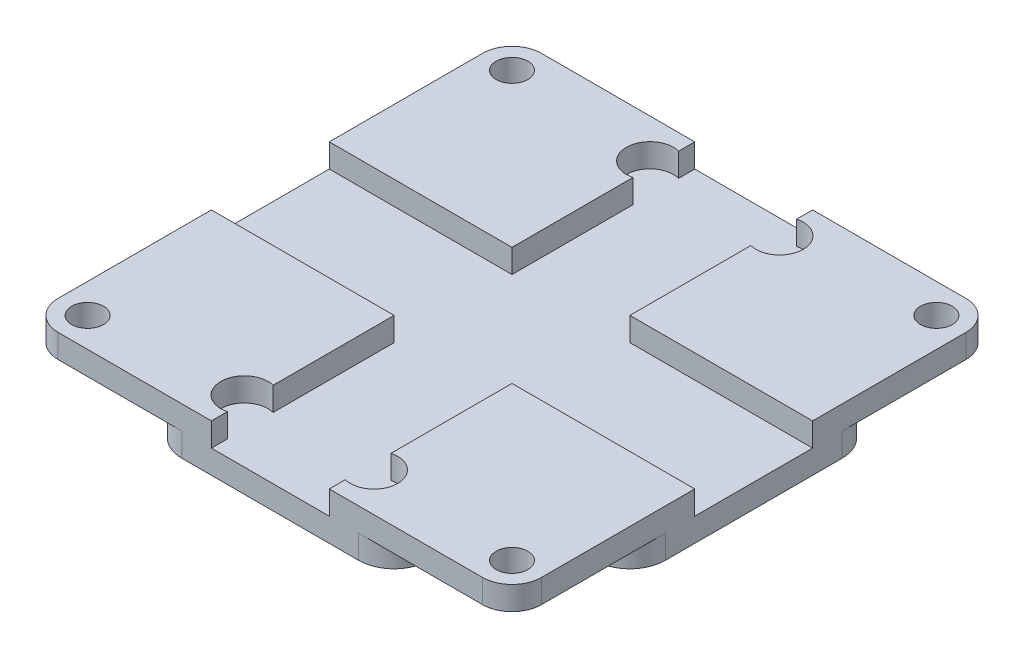
SolidWorks part; units mm, degrees
ref_plane "前视基准面" through (0, 0, 0) normal (0, 0, 1) x (1, 0, 0)
ref_plane "上视基准面" through (0, 0, 0) normal (0, 1, 0) x (1, 0, 0)
ref_plane "右视基准面" through (0, 0, 0) normal (1, 0, 0) x (0, 0, -1)
other "Configuration Table"
sketch "草图1" plane through (0, 0, 0) normal (0, 1, 0) x (1, 0, 0)
  line L1 (2.5, 0) -> (38.5, 0)
  line L2 (0, 2.5) -> (0, 38.5)
  line L3 (2.5, 41) -> (38.5, 41)
  line L4 (41, 2.5) -> (41, 38.5)
  arc A0 (38.5, 0) -> (41, 2.5) centre (38.5, 2.5) ccw
  arc A1 (0, 38.5) -> (2.5, 41) centre (2.5, 38.5) cw
  arc A2 (38.5, 41) -> (41, 38.5) centre (38.5, 38.5) cw
  arc A3 (2.5, 0) -> (0, 2.5) centre (2.5, 2.5) cw
  point P7 (41, 0)
  point P10 (0, 41)
  point P15 (0, 0)
  dimension "D3" = 2.5
  dimension "D1" = 41
  dimension "D2" = 41
extrude "凸台-拉伸1" add sketch "草图1" against normal blind 4 contours L2 A1 L3 A2 L4 A0 L1 A3
sketch "草图2" plane through (0, -4, 0) normal (0, -1, 0) x (1, 0, 0)
  line L0 (20.5, 0) -> (20.5, -41) construction
  line L5 (2.5, 0) -> (0, 0) construction
  line L6 (0, -2.5) -> (0, -38.5) construction
  line L7 (2.5, -41) -> (38.5, -41) construction
  line L8 (2.5, 0) -> (2.5, -2.5) construction
  line L9 (2.5, -2.5) -> (0, -2.5) construction
  line L10 (0, 0) -> (0, -2.5) construction
  line L11 (0, 0) -> (2.5, 0) construction
  line L12 (0, 0) -> (0, -2.5) construction
  line L13 (0, -2.5) -> (2.5, -2.5) construction
  line L14 (2.5, 0) -> (2.5, -2.5) construction
  line L15 (2.5, 0) -> (38.5, 0) construction
  line L16 (41, -20.5) -> (0, -20.5) construction
  line L17 (41, -2.5) -> (41, -38.5) construction
  circle A0 centre (2.5, -2.5) radius 1.35
  circle A1 centre (38.5, -2.5) radius 1.35
  circle A2 centre (2.5, -38.5) radius 1.35
  circle A3 centre (38.5, -38.5) radius 1.35
  point P20 (20.5, -20.5)
extrude "切除-拉伸1" cut sketch "草图2" against normal blind 4
sketch "草图3" plane through (0, -4, 0) normal (0, -1, 0) x (1, 0, 0)
  line L0 (0, -10) -> (0, -13)
  line L1 (0, 0) -> (10, 0)
  line L2 (0, 0) -> (0, -10)
  line L3 (3, -10) -> (7, -10)
  line L4 (10, -3) -> (10, -7)
  line L5 (0, -2.5) -> (0, -38.5) construction
  line L6 (38.5, -2.5) -> (2.5, -38.5) construction
  line L7 (10, 0) -> (13, 0)
  line L9 (10, -3) -> (13, -3) construction
  line L10 (13, 0) -> (13, -3) construction
  line L11 (36, -36) -> (5, -5) construction
  line L12 (41, 0) -> (41, -10)
  line L13 (41, -10) -> (41, -13)
  line L14 (38, -10) -> (34, -10)
  line L15 (31, -3) -> (31, -7)
  line L16 (31, 0) -> (28, 0)
  line L17 (41, 0) -> (31, 0)
  line L18 (41, -41) -> (31, -41)
  line L19 (31, -41) -> (28, -41)
  line L20 (31, -38) -> (31, -34)
  line L21 (38, -31) -> (34, -31)
  line L22 (41, -31) -> (41, -28)
  line L23 (41, -41) -> (41, -31)
  line L24 (0, -41) -> (0, -31)
  line L25 (0, -31) -> (0, -28)
  line L26 (3, -31) -> (7, -31)
  line L27 (10, -38) -> (10, -34)
  line L28 (10, -41) -> (13, -41)
  line L29 (0, -41) -> (10, -41)
  arc A0 (7, -10) -> (10, -7) centre (7, -7) ccw
  arc A1 (3, -10) -> (0, -13) centre (3, -13) ccw
  arc A2 (13, 0) -> (10, -3) centre (13, -3) ccw
  circle A3 centre (20.5, -20.5) radius 0.7475 construction
  arc A4 (41, -13) -> (38, -10) centre (38, -13) ccw
  arc A5 (31, -7) -> (34, -10) centre (34, -7) ccw
  arc A6 (31, -3) -> (28, 0) centre (28, -3) ccw
  arc A7 (28, -41) -> (31, -38) centre (28, -38) ccw
  arc A8 (34, -31) -> (31, -34) centre (34, -34) ccw
  arc A9 (38, -31) -> (41, -28) centre (38, -28) ccw
  arc A10 (0, -28) -> (3, -31) centre (3, -28) ccw
  arc A11 (10, -34) -> (7, -31) centre (7, -34) ccw
  arc A12 (10, -38) -> (13, -41) centre (13, -38) ccw
  point P7 (10, -10)
  point P65 (20.5, -20.5)
  dimension "D3" = 3
  dimension "D1" = 10
  dimension "D2" = 10
  dimension "D4" = 4
extrude "切除-拉伸2" cut sketch "草图3" against normal blind 2
sketch "草图4" plane through (0, 0, 0) normal (0, 1, 0) x (1, 0, 0)
  line L0 (36, 36) -> (5, 5) construction
  line L1 (5, 36) -> (36, 5) construction
  line L2 (-2.5, 15.5) -> (43.5, 15.5)
  line L3 (-2.5, 15.5) -> (-2.5, 25.5)
  line L4 (43.5, 15.5) -> (43.5, 25.5)
  line L5 (-2.5, 25.5) -> (43.5, 25.5)
  line L6 (-2.5, 15.5) -> (43.5, 25.5) construction
  line L7 (43.5, 15.5) -> (-2.5, 25.5) construction
  line L8 (2.5, 0) -> (38.5, 0) construction
  point P8 (20.5, 20.5)
  point P9 (0, 0)
  point P10 (20.5, 20.5)
  point P11 (0, 0)
  point P12 (0, 0)
  dimension "D1" = 5
  dimension "D2" = 15.5
extrude "切除-拉伸3" cut sketch "草图4" against normal blind 2
sketch "草图6" plane through (0, 0, 0) normal (0, 1, 0) x (1, 0, 0)
  line L0 (5, 36) -> (36, 5) construction
  line L1 (36, 36) -> (5, 5) construction
  line L2 (15.5, 15.5) -> (25.5, 15.5) construction
  line L3 (15.5, 15.5) -> (15.5, 25.5) construction
  line L4 (25.5, 15.5) -> (25.5, 25.5) construction
  line L5 (15.5, 25.5) -> (25.5, 25.5) construction
  line L6 (0, 25.5) -> (0, 15.5)
  line L7 (0, 15.5) -> (41, 15.5)
  line L8 (41, 15.5) -> (41, 25.5)
  line L9 (41, 25.5) -> (0, 25.5)
  line L10 (0, 25.5) -> (0, 15.5) construction
  line L11 (0, 15.5) -> (41, 15.5) construction
  line L12 (41, 15.5) -> (41, 25.5) construction
  line L13 (41, 25.5) -> (0, 25.5) construction
  line L14 (15.5, 15.5) -> (25.5, 25.5) construction
  line L15 (25.5, 15.5) -> (15.5, 25.5) construction
  line L16 (25.5, 20.5) -> (15.5, 20.5) construction
  line L17 (15.5, 25.5) -> (25.5, 25.5)
  line L18 (15.5, 25.5) -> (15.5, 50.5)
  line L19 (15.5, 50.5) -> (25.5, 50.5)
  line L20 (25.5, 25.5) -> (25.5, 50.5)
  line L21 (15.5, -9.5) -> (25.5, -9.5)
  line L22 (25.5, 15.5) -> (25.5, -9.5)
  line L23 (15.5, 15.5) -> (25.5, 15.5)
  line L24 (15.5, 15.5) -> (15.5, -9.5)
  line L25 (41, 2.5) -> (41, 15.5) construction
  line L26 (0, 15.5) -> (41, 15.5) construction
  point P8 (20.5, 20.5)
  point P13 (20.5, 20.5)
  dimension "D2" = 35
  dimension "D1" = 0
extrude "切除-拉伸4" cut sketch "草图6" against normal blind 2
sketch "草图7" plane through (0, 0, 0) normal (0, 1, 0) x (1, 0, 0)
  line L0 (36, 36) -> (5, 5) construction
  line L1 (0, 38.5) -> (2.5, 38.5) construction
  line L2 (0, 38.5) -> (0, 41) construction
  line L3 (0, 41) -> (2.5, 41) construction
  line L4 (2.5, 38.5) -> (2.5, 41) construction
  line L5 (0, 41) -> (15, 41) construction
  line L6 (0, 41) -> (0, 37.7) construction
  line L7 (0, 37.7) -> (15, 37.7) construction
  line L8 (15, 41) -> (15, 37.7) construction
  line L9 (36, 5) -> (2.5, 38.5) construction
  line L10 (20.5, 20.5) -> (20.5, 0) construction
  line L11 (2.5, 0) -> (15.5, 0) construction
  arc A0 (2.5, 41) -> (0, 38.5) centre (2.5, 38.5) ccw construction
  arc A1 (2.5, 41) -> (0, 38.5) centre (2.5, 38.5) ccw construction
  circle A2 centre (15, 37.7) radius 2
  circle A3 centre (26, 3.3) radius 2
  circle A4 centre (26, 37.7) radius 2
  circle A5 centre (15, 3.3) radius 2
  point P12 (19.25, 21.75)
  point P19 (20.5, 20.5)
  dimension "D3" = 4
  dimension "D1" = 15
  dimension "D2" = 3.3
  dimension "D4" = 2
extrude "切除-拉伸5" cut sketch "草图7" against normal blind 2
